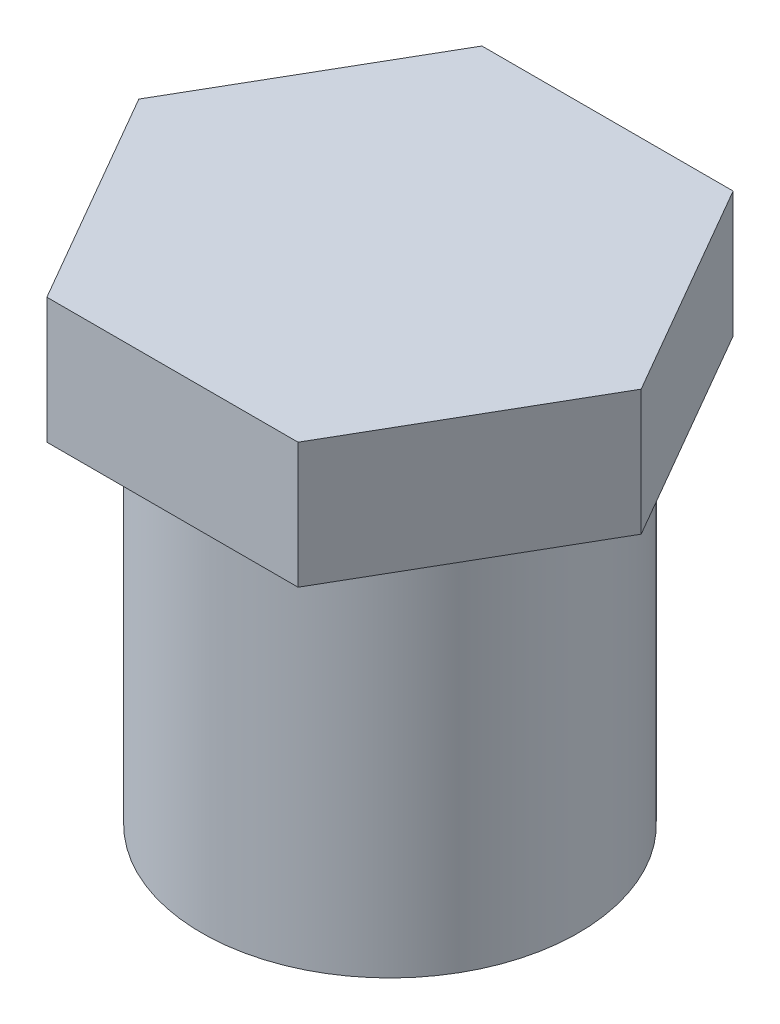
SolidWorks part; units mm, degrees
ref_plane "Front Plane" through (0, 0, 0) normal (0, 0, 1) x (1, 0, 0)
ref_plane "Top Plane" through (0, 0, 0) normal (0, 1, 0) x (1, 0, 0)
ref_plane "Right Plane" through (0, 0, 0) normal (1, 0, 0) x (0, 0, -1)
sketch "Sketch1" plane through (0, 0, 0) normal (0, 1, 0) x (1, 0, 0)
  circle A0 centre (0, 0) radius 1.905
  dimension "D1" = 3.81
extrude "Boss-Extrude1" add sketch "Sketch1" along normal blind 3.81
sketch "Sketch2" plane through (0, 3.81, 0) normal (0, 1, 0) x (1, 0, 0)
  line L1 (1.27, 2.1997) -> (-1.27, 2.1997)
  line L2 (-1.27, 2.1997) -> (-2.54, 0)
  line L3 (-2.54, 0) -> (-1.27, -2.1997)
  line L4 (-1.27, -2.1997) -> (1.27, -2.1997)
  line L5 (1.27, -2.1997) -> (2.54, 0)
  line L6 (2.54, 0) -> (1.27, 2.1997)
  circle A0 centre (0, 0) radius 2.1997 construction
  point P1 (-2.54, 0)
  dimension "D1" = 2.54
extrude "Boss-Extrude2" add sketch "Sketch2" along normal blind 1.27
